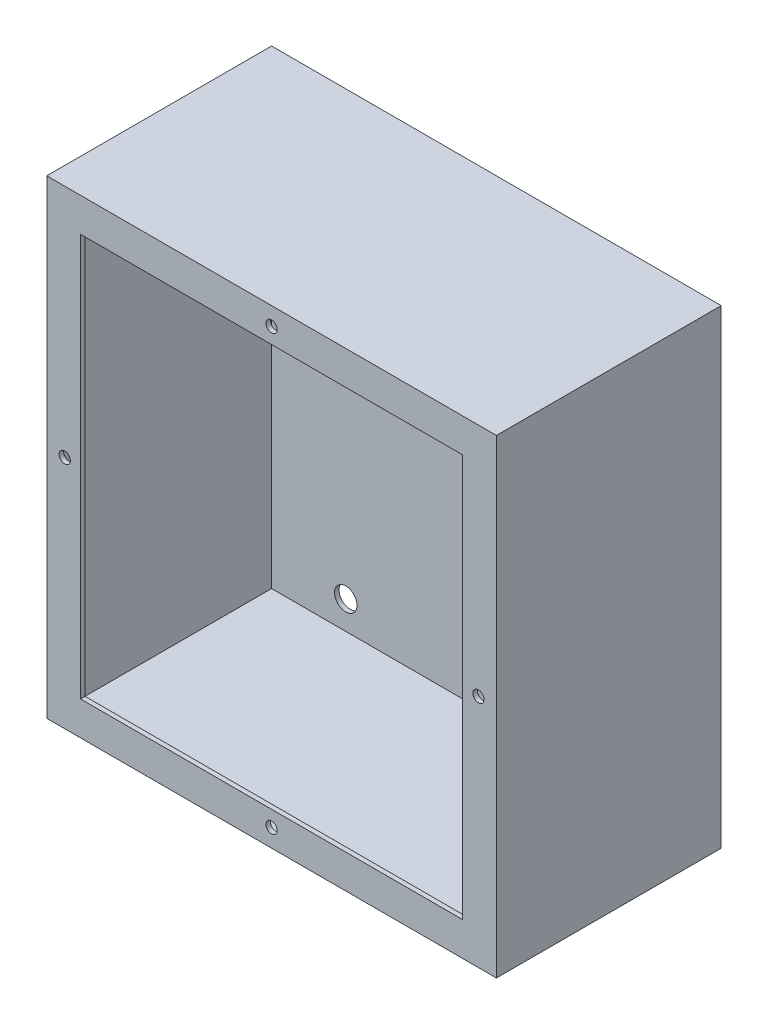
SolidWorks part; units mm, degrees
ref_plane "前视基准面" through (0, 0, 0) normal (0, 0, 1) x (1, 0, 0)
ref_plane "上视基准面" through (0, 0, 0) normal (0, 1, 0) x (1, 0, 0)
ref_plane "右视基准面" through (0, 0, 0) normal (1, 0, 0) x (0, 0, -1)
sketch "草图1" plane through (0, 0, 0) normal (0, 0, 1) x (1, 0, 0)
  line L1 (0, 0) -> (200, 0)
  line L2 (0, 0) -> (0, -209)
  line L3 (0, -209) -> (200, -209)
  line L4 (200, 0) -> (200, -209)
  dimension "D1" = 200
  dimension "D2" = 209
extrude "拉伸1" add sketch "草图1" along normal blind 100
shell "抽壳1" thickness 2
sketch "草图2" plane through (0, 0, 100) normal (0, 0, 1) x (1, 0, 0)
  line L5 (2, -2) -> (198, -2)
  line L6 (2, -2) -> (2, -207)
  line L7 (2, -207) -> (198, -207)
  line L8 (198, -2) -> (198, -207)
  line L16 (15, -15) -> (15, -194)
  line L17 (15, -194) -> (185, -194)
  line L18 (185, -194) -> (185, -15)
  line L19 (185, -15) -> (15, -15)
  line L20 (15, -15) -> (15, -194)
  line L21 (15, -194) -> (185, -194)
  line L22 (185, -194) -> (185, -15)
  line L23 (185, -15) -> (15, -15)
  dimension "D2" = 15
extrude "拉伸2" add sketch "草图2" against normal blind 2
sketch "草图3" plane through (0, 0, 0) normal (0, 0, -1) x (-1, 0, 0)
  line L9 (-165, -14.5) -> (-35, -14.5) construction
  line L10 (-165, -14.5) -> (-165, -194.5) construction
  circle A0 centre (-165, -14.5) radius 5
  circle A1 centre (-35, -14.5) radius 5
  circle A2 centre (-165, -194.5) radius 5
  circle A3 centre (-35, -194.5) radius 5
  dimension "D5" = 90
  dimension "D1" = 10
  dimension "D3" = 130
extrude "切除-拉伸1" cut sketch "草图3" against normal blind 22
sketch "草图4" plane through (0, 0, 100) normal (0, 0, 1) x (1, 0, 0)
  line L13 (200, 0) -> (0, 0) construction
  line L14 (0, -209) -> (200, -209) construction
  line L15 (200, -209) -> (200, 0) construction
  line L16 (0, 0) -> (0, -209) construction
  circle A0 centre (100, -8) radius 2.5
  circle A1 centre (192, -104.5) radius 2.5
  circle A2 centre (8, -104.5) radius 2.5
  circle A3 centre (100, -201) radius 2.5
  dimension "D2" = 8
  dimension "D1" = 8
  dimension "D3" = 8
  dimension "D4" = 8
  dimension "D5" = 5
  dimension "D6" = 5
  dimension "D7" = 5
  dimension "D8" = 5
extrude "切除-拉伸2" cut sketch "草图4" against normal blind 10
